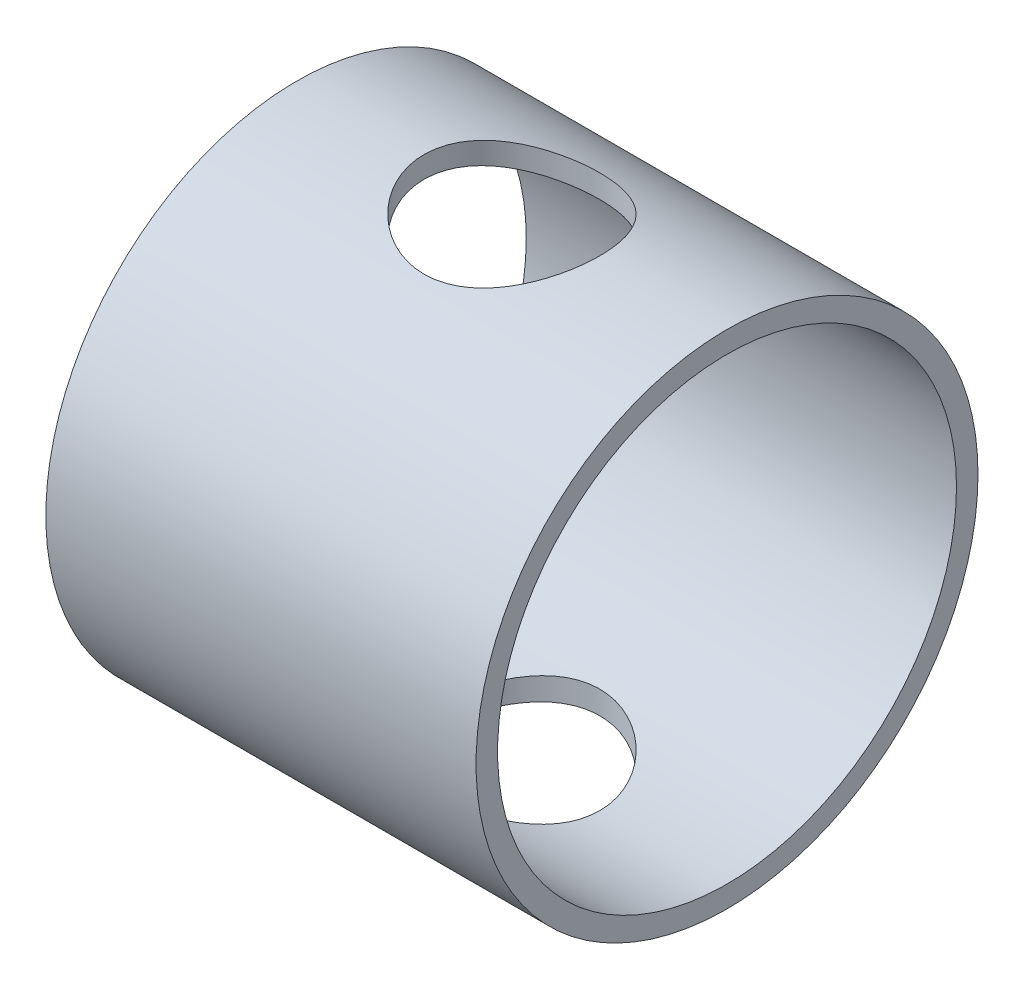
SolidWorks part; units mm, degrees
ref_plane "Front Plane" through (0, 0, 0) normal (0, 0, 1) x (1, 0, 0)
ref_plane "Top Plane" through (0, 0, 0) normal (0, 1, 0) x (1, 0, 0)
ref_plane "Right Plane" through (0, 0, 0) normal (1, 0, 0) x (0, 0, -1)
sketch "Sketch1" plane through (0, 0, 0) normal (1, 0, 0) x (0, 0, -1)
  circle A0 centre (0, 0) radius 32
  circle A1 centre (0, 0) radius 35
  dimension "D1" = 64
  dimension "D2" = 70
extrude "Boss-Extrude1" add sketch "Sketch1" along normal blind 60
sketch "Sketch2" plane through (0, 0, 0) normal (0, 1, 0) x (1, 0, 0)
  line L0 (0, 0) -> (60, 0) construction
  line L1 (60, -35) -> (60, 35) construction
  circle A0 centre (30, 0) radius 12.25
  dimension "D1" = 24.5
extrude "Cut-Extrude1" cut sketch "Sketch2" against normal through all both and the other way through all
